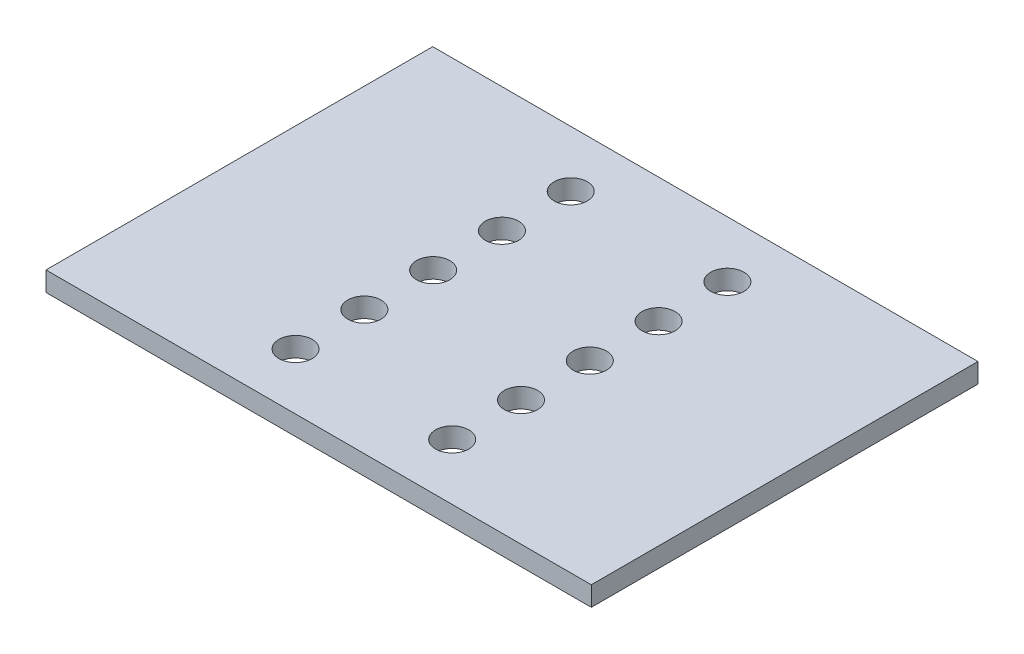
SolidWorks part; units mm, degrees
ref_plane "Front Plane" through (0, 0, 0) normal (0, 0, 1) x (1, 0, 0)
ref_plane "Top Plane" through (0, 0, 0) normal (0, 1, 0) x (1, 0, 0)
ref_plane "Right Plane" through (0, 0, 0) normal (1, 0, 0) x (0, 0, -1)
sketch "Sketch1" plane through (0, 0, 0) normal (0, 1, 0) x (1, 0, 0)
  line L1 (27.85, 19.75) -> (-27.85, 19.75)
  line L2 (27.85, 19.75) -> (27.85, -19.75)
  line L3 (27.85, -19.75) -> (-27.85, -19.75)
  line L4 (-27.85, 19.75) -> (-27.85, -19.75)
  line L5 (27.85, 19.75) -> (-27.85, -19.75) construction
  line L6 (27.85, -19.75) -> (-27.85, 19.75) construction
  point P0 (0, 0)
  dimension "D1" = 55.7
  dimension "D2" = 39.5
extrude "Boss-Extrude1" add sketch "Sketch1" along normal blind 2 contours L1 L4 L3 L2
sketch "Sketch2" plane through (0, 2, 0) normal (0, 1, 0) x (1, 0, 0)
  line L0 (27.85, 19.75) -> (27.85, -19.75) construction
  line L4 (0, 0) -> (0, 7) construction
  line L11 (-8, 0) -> (-8, 14) construction
  line L12 (-8, 0) -> (8, 14) construction
  line L13 (8, 0) -> (-8, 14) construction
  line L14 (-8, 0) -> (-8, 14) construction
  line L15 (-8, 0) -> (8, 0) construction
  line L16 (8, 0) -> (8, 14) construction
  line L17 (-8, 14) -> (8, 14) construction
  line L18 (-8, 0) -> (8, 14) construction
  line L19 (8, 0) -> (-8, 14) construction
  circle A5 centre (-8, 0) radius 1.7 construction
  circle A6 centre (-8, 14) radius 1.7
  circle A7 centre (8, 14) radius 1.7
  circle A8 centre (8, 0) radius 1.7 construction
  circle A9 centre (7.9727, 7.0001) radius 1.7
  circle A10 centre (-8.0273, 7.0001) radius 1.7
  circle A11 centre (7.9454, 0.0001) radius 1.7
  circle A12 centre (-8.0546, 0.0001) radius 1.7
  circle A13 centre (7.9181, -6.9998) radius 1.7
  circle A14 centre (-8.0819, -6.9998) radius 1.7
  circle A15 centre (7.8908, -13.9998) radius 1.7
  circle A16 centre (-8.1092, -13.9998) radius 1.7
  point P8 (0, 7)
  dimension "D3" = 5
  dimension "D2" = 3.4
  dimension "D1" = 7
  dimension "D5" = 14
  dimension "D6" = 16
extrude "Cut-Extrude2" cut sketch "Sketch2" against normal through all
